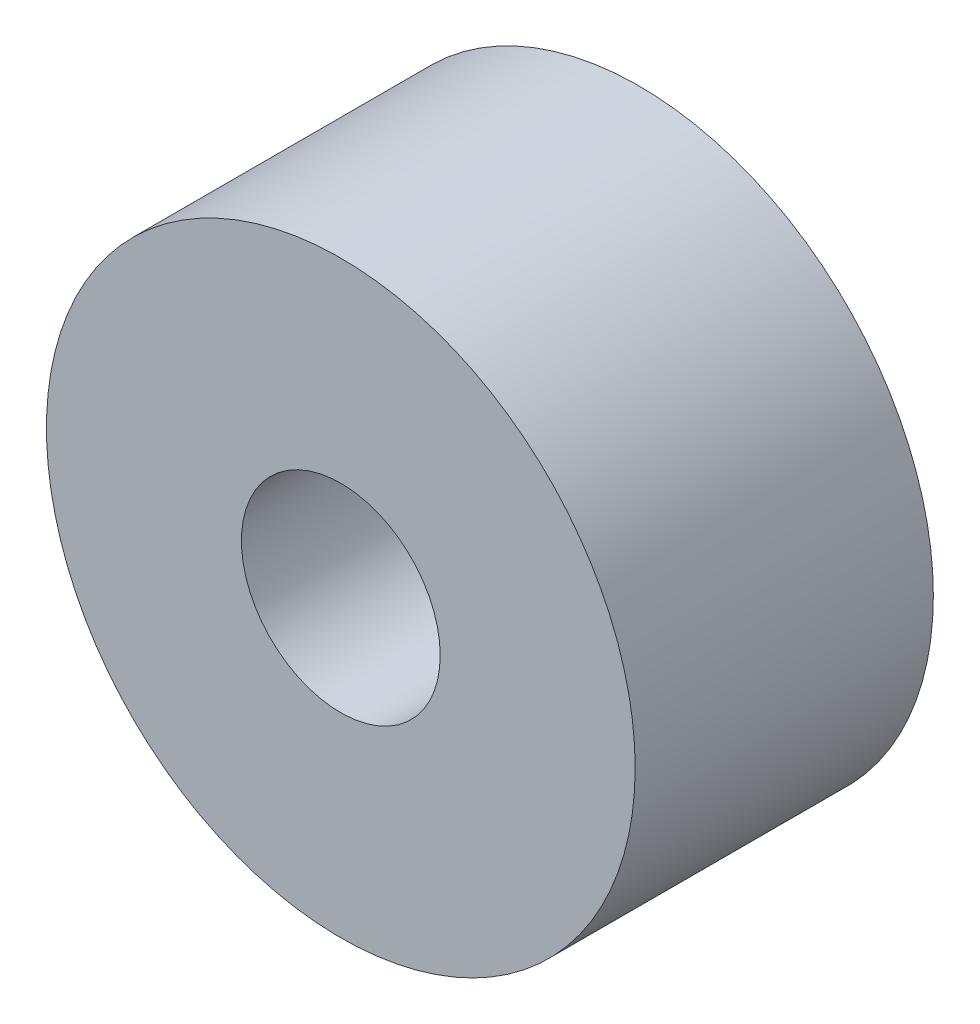
SolidWorks part; units mm, degrees
ref_plane "Спереди" through (0, 0, 0) normal (0, 0, 1) x (1, 0, 0)
ref_plane "Сверху" through (0, 0, 0) normal (0, 1, 0) x (1, 0, 0)
ref_plane "Справа" through (0, 0, 0) normal (1, 0, 0) x (0, 0, -1)
sketch "Эскиз1" plane through (0, 0, 0) normal (0, 0, 1) x (1, 0, 0)
  circle A0 centre (0, 0) radius 29.6154
  circle A1 centre (0, 0) radius 10
extrude "Carrier" add sketch "Эскиз1" along normal blind 30 from offset 15
